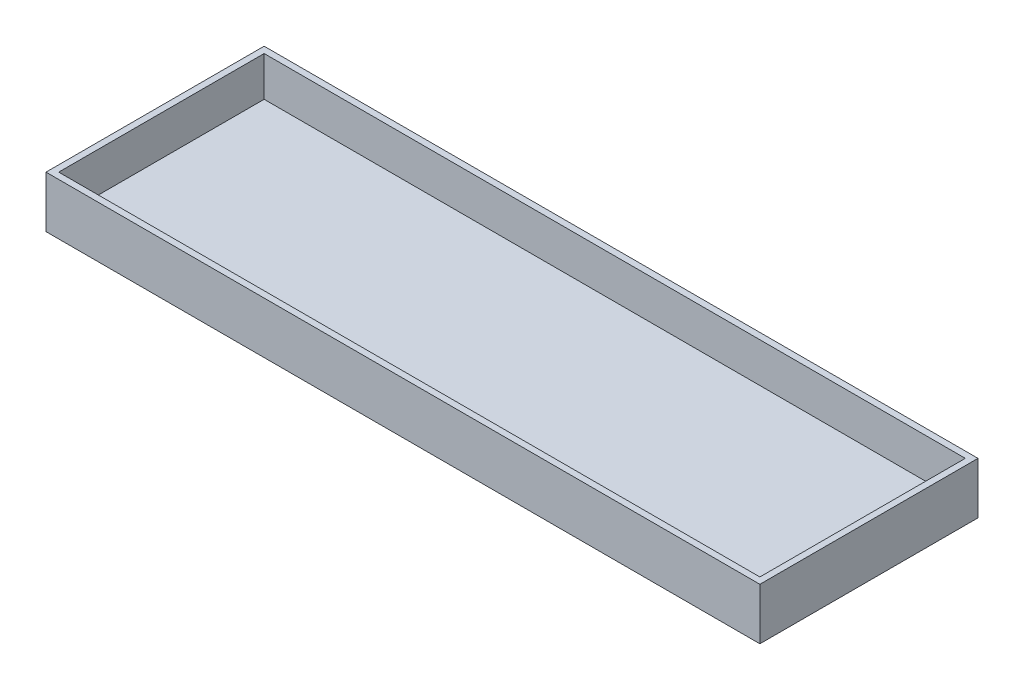
SolidWorks part; units mm, degrees
ref_plane "Front Plane" through (0, 0, 0) normal (0, 0, 1) x (1, 0, 0)
ref_plane "Top Plane" through (0, 0, 0) normal (0, 1, 0) x (1, 0, 0)
ref_plane "Right Plane" through (0, 0, 0) normal (1, 0, 0) x (0, 0, -1)
sketch "Sketch1" plane through (0, 0, 0) normal (0, 1, 0) x (1, 0, 0)
  line L1 (-90, 27.5) -> (90, 27.5)
  line L2 (-90, 27.5) -> (-90, -27.5)
  line L3 (-90, -27.5) -> (90, -27.5)
  line L4 (90, 27.5) -> (90, -27.5)
  line L5 (-90, 27.5) -> (90, -27.5) construction
  line L6 (-90, -27.5) -> (90, 27.5) construction
  point P0 (0, 0)
  dimension "D1" = 180
  dimension "D2" = 55
extrude "Boss-Extrude1" add sketch "Sketch1" along normal blind 3
sketch "Sketch2" plane through (0, 3, 0) normal (0, 1, 0) x (1, 0, 0)
  line L1 (-88.4, 25.9) -> (88.4, 25.9)
  line L2 (-88.4, 25.9) -> (-88.4, -25.9)
  line L3 (-88.4, -25.9) -> (88.4, -25.9)
  line L4 (88.4, 25.9) -> (88.4, -25.9)
  line L5 (-88.4, 25.9) -> (88.4, -25.9) construction
  line L6 (-88.4, -25.9) -> (88.4, 25.9) construction
  line L10 (90, -27.5) -> (90, 27.5)
  line L11 (90, 27.5) -> (-90, 27.5)
  line L12 (-90, 27.5) -> (-90, -27.5)
  line L13 (-90, -27.5) -> (90, -27.5)
  line L14 (90, -27.5) -> (90, 27.5)
  line L15 (90, 27.5) -> (-90, 27.5)
  line L16 (-90, 27.5) -> (-90, -27.5)
  line L17 (-90, -27.5) -> (90, -27.5)
  point P0 (0, 0)
  dimension "D2" = 1.6
  dimension "D3" = 1.6
  dimension "D1" = 0
extrude "Boss-Extrude2" add sketch "Sketch2" along normal blind 10
